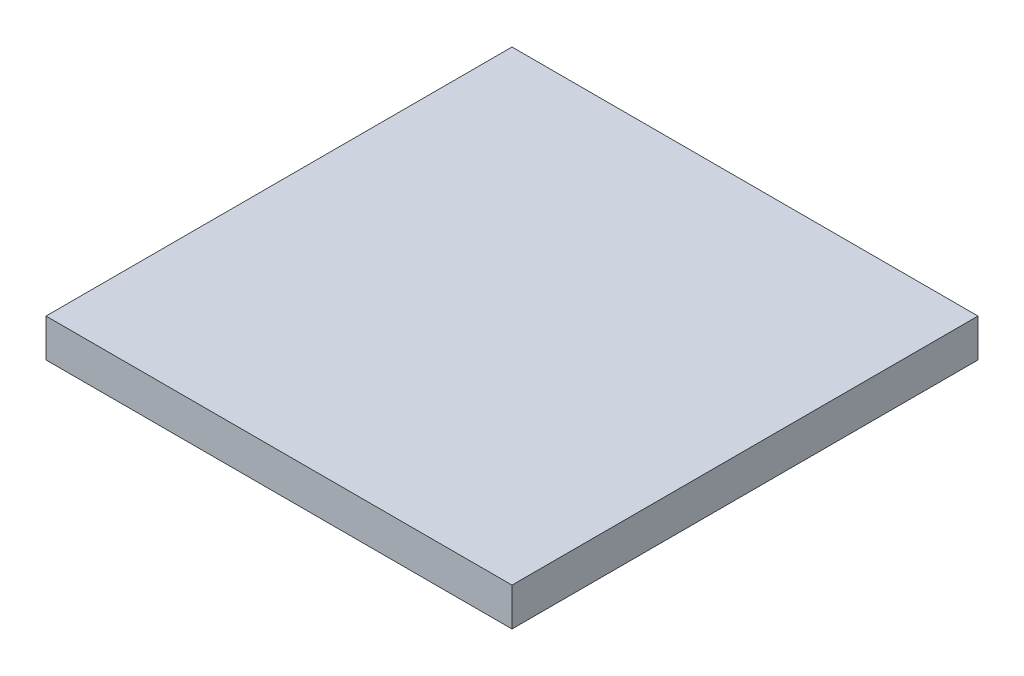
SolidWorks part; units mm, degrees
ref_plane "Front Plane" through (0, 0, 0) normal (0, 0, 1) x (1, 0, 0)
ref_plane "Top Plane" through (0, 0, 0) normal (0, 1, 0) x (1, 0, 0)
ref_plane "Right Plane" through (0, 0, 0) normal (1, 0, 0) x (0, 0, -1)
sketch "Sketch1" plane through (0, 0, 0) normal (0, 1, 0) x (1, 0, 0)
  line L1 (0, 0) -> (24.5, 0)
  line L2 (0, 0) -> (0, 24.5)
  line L3 (0, 24.5) -> (24.5, 24.5)
  line L4 (24.5, 0) -> (24.5, 24.5)
  dimension "D1" = 24.5
  dimension "D2" = 24.5
extrude "Boss-Extrude1" add sketch "Sketch1" along normal blind 2
